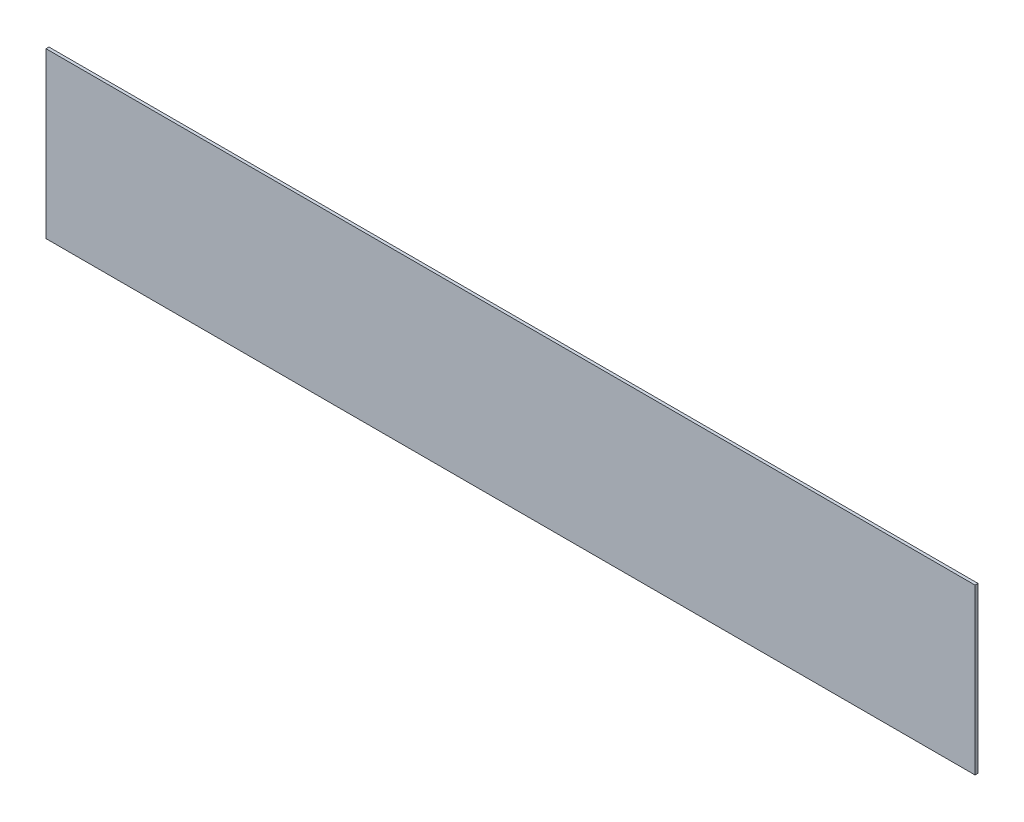
SolidWorks part; units mm, degrees
ref_plane "Front Plane" through (0, 0, 0) normal (0, 0, 1) x (1, 0, 0)
ref_plane "Top Plane" through (0, 0, 0) normal (0, 1, 0) x (1, 0, 0)
ref_plane "Right Plane" through (0, 0, 0) normal (1, 0, 0) x (0, 0, -1)
sketch "Sketch1" plane through (0, 0, 0) normal (0, 0, 1) x (1, 0, 0)
  line L0 (0, -88.519) -> (25.4, -88.519) construction
  line L1 (0, 0) -> (1000, 0)
  line L2 (0, 0) -> (0, -177.038)
  line L3 (0, -177.038) -> (1000, -177.038)
  line L4 (1000, 0) -> (1000, -177.038)
  dimension "D1" = 1000
  dimension "D2" = 177.038
extrude "Boss-Extrude1" add sketch "Sketch1" along normal blind 3.175
sketch "Sketch2" plane through (0, -177.038, 0) normal (0, -1, 0) x (1, 0, 0)
  line L0 (1000, 1.5875) -> (0, 1.5875) construction
  line L1 (1000, 3.175) -> (1000, 0) construction
  line L2 (0, 3.175) -> (0, 0) construction
sketch "Sketch4" plane through (0, 0, 0) normal (0, 1, 0) x (1, 0, 0)
  line L0 (-998.528, -1.5875) -> (998.528, -1.5875) construction
  point P3 (0, -1.5875)
sketch "Sketch5" plane through (1000, 0, 0) normal (1, 0, 0) x (0, 0, -1)
  line L0 (-1.5875, 0) -> (-1.5875, -177.038) construction
  line L1 (-3.175, 0) -> (0, 0) construction
  line L2 (-3.175, -177.038) -> (0, -177.038) construction
sketch "Sketch6" plane through (0, 0, 0) normal (-1, 0, 0) x (0, 0, 1)
  line L0 (1.5875, 0) -> (1.5875, -177.038) construction
  line L1 (3.175, -177.038) -> (0, -177.038) construction
